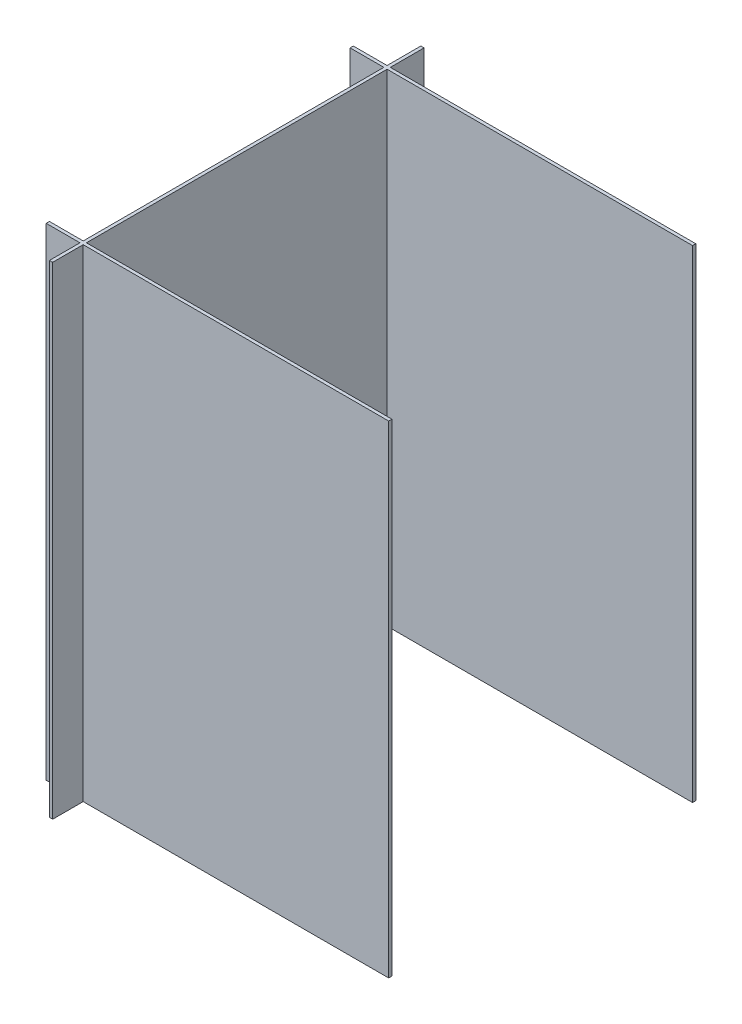
SolidWorks part; units mm, degrees
ref_plane "Front Plane" through (0, 0, 0) normal (0, 0, 1) x (1, 0, 0)
ref_plane "Top Plane" through (0, 0, 0) normal (0, 1, 0) x (1, 0, 0)
ref_plane "Right Plane" through (0, 0, 0) normal (1, 0, 0) x (0, 0, -1)
sketch "Sketch1" plane through (0, 0, 0) normal (0, 1, 0) x (1, 0, 0)
  line L0 (-56.1616, -42.3023) -> (-35.1616, -42.3023)
  line L1 (-33.1616, -42.3023) -> (156.8384, -42.3023)
  line L2 (-56.1616, -233.3023) -> (-35.1616, -233.3023)
  line L3 (-33.1616, -233.3023) -> (156.8384, -233.3023)
  line L4 (-35.1616, -42.3023) -> (-35.1616, -21.3023)
  line L5 (-33.1616, -42.3023) -> (-33.1616, -21.3023)
  line L6 (-35.1616, -233.3023) -> (-35.1616, -252.3023)
  line L7 (-33.1616, -233.3023) -> (-33.1616, -252.3023)
  line L8 (-56.1616, -44.3023) -> (-35.1616, -44.3023)
  line L9 (-33.1616, -44.3023) -> (156.8384, -44.3023)
  line L10 (-33.1616, -44.3023) -> (-33.1616, -231.3023)
  line L11 (-33.1616, -231.3023) -> (156.8384, -231.3023)
  line L12 (156.8384, -231.3023) -> (156.8384, -233.3023)
  line L13 (-56.1616, -42.3023) -> (-56.1616, -44.3023)
  line L14 (-35.1616, -44.3023) -> (-35.1616, -231.3023)
  line L15 (-35.1616, -231.3023) -> (-56.1616, -231.3023)
  line L16 (-56.1616, -231.3023) -> (-56.1616, -233.3023)
  line L17 (156.8384, -42.3023) -> (156.8384, -44.3023)
  line L18 (-35.1616, -21.3023) -> (-33.1616, -21.3023)
  line L20 (-35.1616, -252.3023) -> (-33.1616, -252.3023)
  dimension "D1" = 191
  dimension "D2" = 2
  dimension "D3" = 2
  dimension "D4" = 2
  dimension "D5" = 2
  dimension "D6" = 21
  dimension "D7" = 21
  dimension "D8" = 192
  dimension "D9" = 23
extrude "Boss-Extrude1" add sketch "Sketch1" along normal blind 300
